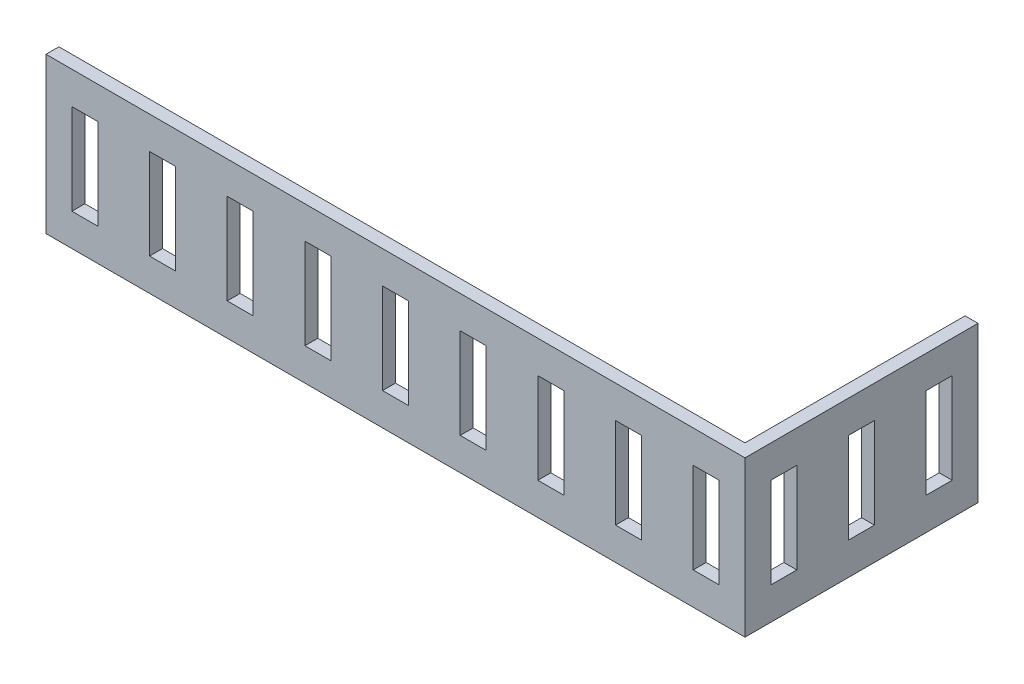
SolidWorks part; units mm, degrees
ref_plane "前视基准面" through (0, 0, 0) normal (0, 0, 1) x (1, 0, 0)
ref_plane "上视基准面" through (0, 0, 0) normal (0, 1, 0) x (1, 0, 0)
ref_plane "右视基准面" through (0, 0, 0) normal (1, 0, 0) x (0, 0, -1)
sketch "草图1" plane through (0, 0, 0) normal (0, 1, 0) x (1, 0, 0)
  line L0 (0, 0) -> (26.5, 0)
  line L1 (26.5, 0) -> (26.5, 8.5)
  line L2 (0, -0.5) -> (27, -0.5)
  line L3 (27, -0.5) -> (27, 8.5)
  line L4 (26.5, 8.5) -> (27, 8.5)
  line L5 (0, 0) -> (0, -0.5)
  dimension "D1" = 26.5
  dimension "D2" = 8.5
  dimension "D3" = 0.5
extrude "凸台-拉伸1" add sketch "草图1" along normal blind 6
sketch "草图2" plane through (0, 0, 0.5) normal (0, 0, 1) x (1, 0, 0)
  line L0 (0, 6) -> (27, 6) construction
  line L1 (1, 4.75) -> (2, 4.75)
  line L2 (1, 4.75) -> (1, 1.25)
  line L3 (1, 1.25) -> (2, 1.25)
  line L4 (2, 4.75) -> (2, 1.25)
  line L5 (0, 6) -> (0, 0) construction
  line L6 (4, 4.75) -> (4, 1.25)
  line L7 (4, 4.75) -> (5, 4.75)
  line L8 (5, 4.75) -> (5, 1.25)
  line L9 (4, 1.25) -> (5, 1.25)
  line L10 (7, 4.75) -> (7, 1.25)
  line L11 (7, 4.75) -> (8, 4.75)
  line L12 (8, 4.75) -> (8, 1.25)
  line L13 (7, 1.25) -> (8, 1.25)
  line L14 (10, 4.75) -> (10, 1.25)
  line L15 (10, 4.75) -> (11, 4.75)
  line L16 (11, 4.75) -> (11, 1.25)
  line L17 (10, 1.25) -> (11, 1.25)
  line L18 (13, 4.75) -> (13, 1.25)
  line L19 (13, 4.75) -> (14, 4.75)
  line L20 (14, 4.75) -> (14, 1.25)
  line L21 (13, 1.25) -> (14, 1.25)
  line L22 (16, 4.75) -> (16, 1.25)
  line L23 (16, 4.75) -> (17, 4.75)
  line L24 (17, 4.75) -> (17, 1.25)
  line L25 (16, 1.25) -> (17, 1.25)
  line L26 (19, 4.75) -> (19, 1.25)
  line L27 (19, 4.75) -> (20, 4.75)
  line L28 (20, 4.75) -> (20, 1.25)
  line L29 (19, 1.25) -> (20, 1.25)
  line L30 (22, 4.75) -> (22, 1.25)
  line L31 (22, 4.75) -> (23, 4.75)
  line L32 (23, 4.75) -> (23, 1.25)
  line L33 (22, 1.25) -> (23, 1.25)
  line L34 (25, 4.75) -> (25, 1.25)
  line L35 (25, 4.75) -> (26, 4.75)
  line L36 (26, 4.75) -> (26, 1.25)
  line L37 (25, 1.25) -> (26, 1.25)
  point P4 (1.5, 4.75)
  dimension "D1" = 3.5
  dimension "D2" = 1
  dimension "D3" = 1.25
  dimension "D4" = 1
  dimension "D5" = 9
extrude "切除-拉伸1" cut sketch "草图2" against normal through all
sketch "草图3" plane through (27, 0, 0) normal (1, 0, 0) x (0, 0, -1)
  line L1 (0.5, 4.75) -> (1.5, 4.75)
  line L2 (0.5, 4.75) -> (0.5, 1.25)
  line L3 (0.5, 1.25) -> (1.5, 1.25)
  line L4 (1.5, 4.75) -> (1.5, 1.25)
  line L5 (-0.5, 6) -> (-0.5, 0) construction
  line L6 (0, 4.75) -> (-0.5, 4.75) construction
  line L7 (3.5, 4.75) -> (3.5, 1.25)
  line L8 (3.5, 4.75) -> (4.5, 4.75)
  line L9 (4.5, 4.75) -> (4.5, 1.25)
  line L10 (3.5, 1.25) -> (4.5, 1.25)
  line L11 (6.5, 4.75) -> (6.5, 1.25)
  line L12 (6.5, 4.75) -> (7.5, 4.75)
  line L13 (7.5, 4.75) -> (7.5, 1.25)
  line L14 (6.5, 1.25) -> (7.5, 1.25)
  dimension "D1" = 1
  dimension "D2" = 3.5
  dimension "D3" = 3
  dimension "D4" = 1
extrude "切除-拉伸2" cut sketch "草图3" against normal blind 6
